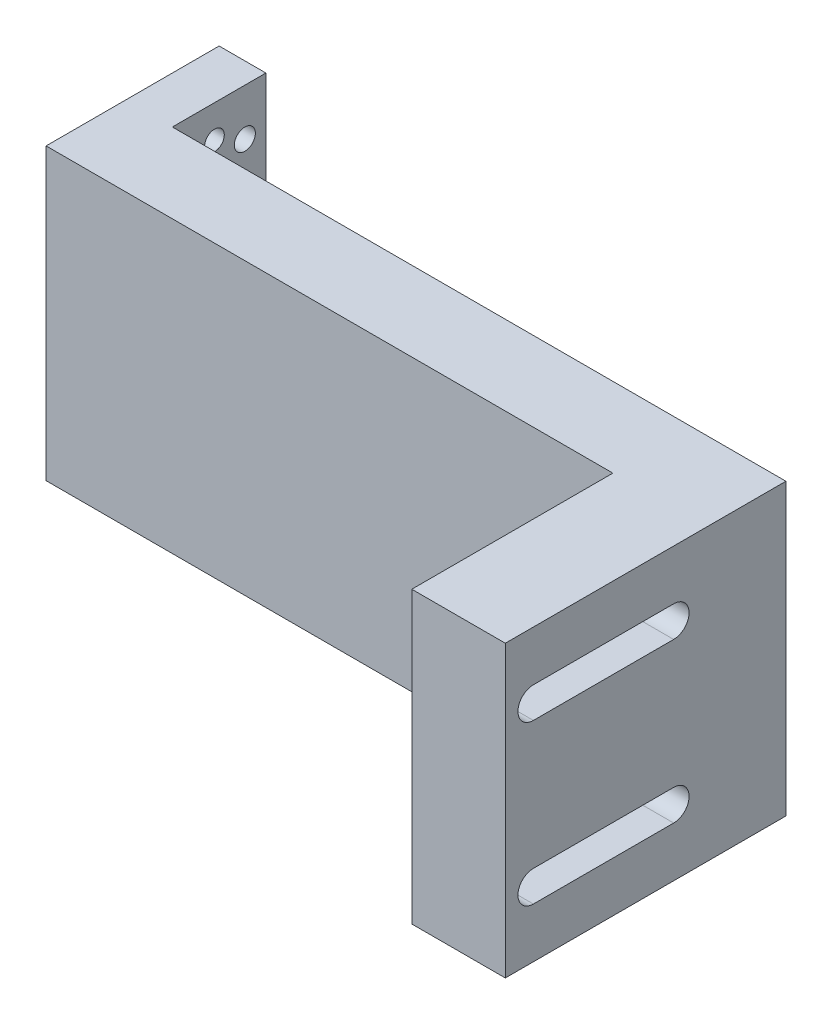
SolidWorks part; units mm, degrees
material "铝材"
ref_plane "前基準面" through (0, 0, 0) normal (0, 0, 1) x (1, 0, 0)
ref_plane "上基準面" through (0, 0, 0) normal (0, 1, 0) x (1, 0, 0)
ref_plane "右基準面" through (0, 0, 0) normal (1, 0, 0) x (0, 0, -1)
sketch "草图1" plane through (0, 0, 0) normal (0, 0, 1) x (1, 0, 0)
  line L1 (0, 0) -> (141.2, 0)
  line L2 (0, 0) -> (0, 62)
  line L3 (0, 62) -> (141.2, 62)
  line L4 (141.2, 0) -> (141.2, 62)
  dimension "D1" = 141.2
  dimension "D2" = 62
extrude "凸台-拉伸1" add sketch "草图1" along normal blind 80
sketch "草图2" plane through (0, 0, 0) normal (0, -1, 0) x (1, 0, 0)
  line L0 (0, 0) -> (141.2, 0) construction
  line L1 (10, 0) -> (141.2, 0)
  line L2 (10, 0) -> (10, 20)
  line L3 (10, 20) -> (141.2, 20)
  line L4 (141.2, 0) -> (141.2, 20)
  line L5 (141.2, 80) -> (141.2, 0) construction
  line L6 (0, 80) -> (0, 0) construction
  line L7 (0, 80) -> (121.2, 80)
  line L8 (0, 80) -> (0, 37)
  line L9 (0, 37) -> (121.2, 37)
  line L10 (121.2, 80) -> (121.2, 37)
  dimension "D1" = 10
  dimension "D2" = 20
  dimension "D3" = 17
  dimension "D4" = 20
extrude "切除-拉伸1" cut sketch "草图2" against normal through all
sketch "草图3" plane through (121.2, 0, 0) normal (-1, 0, 0) x (0, 0, 1)
  line L0 (44, 14) -> (74, 14) construction
  line L1 (44, 17.3) -> (74, 17.3)
  line L2 (44, 10.7) -> (74, 10.7)
  line L3 (80, 31) -> (37, 31) construction
  line L4 (80, 62) -> (80, 0) construction
  line L5 (37, 62) -> (37, 0) construction
  line L6 (44, 48) -> (74, 48) construction
  line L7 (44, 44.7) -> (74, 44.7)
  line L8 (44, 51.3) -> (74, 51.3)
  arc A0 (44, 17.3) -> (44, 10.7) centre (44, 14) ccw
  arc A1 (74, 10.7) -> (74, 17.3) centre (74, 14) ccw
  arc A2 (44, 44.7) -> (44, 51.3) centre (44, 48) cw
  arc A3 (74, 51.3) -> (74, 44.7) centre (74, 48) cw
  point P2 (59, 14)
  point P15 (59, 48)
  dimension "D2" = 6
  dimension "D1" = 6.6
  dimension "D3" = 30
  dimension "D4" = 34
extrude "切除-拉伸2" cut sketch "草图3" against normal blind 70
sketch "草图4" plane through (10, 0, 0) normal (1, 0, 0) x (0, 0, -1)
  line L0 (0, 31) -> (-20, 31) construction
  line L1 (0, 62) -> (0, 0) construction
  line L2 (-20, 62) -> (-20, 0) construction
  circle A0 centre (-4.5, 10) radius 2.25
  circle A1 centre (-4.5, 52) radius 2.25
  dimension "D1" = 4.5
  dimension "D2" = 4.5
  dimension "D3" = 42
extrude "切除-拉伸3" cut sketch "草图4" against normal through all
hole_wizard "M5 螺纹孔1" positions "草图6" profile "草图5" tap size "M5" standard "ISO"
sketch "草图6" plane through (0, 0, 0) normal (-1, 0, 0) x (0, 0, 1)
  point P0 (29, 7)
  point P1 (11, 7)
  point P4 (11, 55)
  point P7 (29, 55)
sketch "草图5" plane through (0, 7, 29) normal (0, 1, 0) x (0, 0, 1)
  line L0 (0, 0) -> (0, 13.6618)
  line L1 (0, 13.6618) -> (2.1, 12.4)
  line L2 (2.1, 12.4) -> (2.1, 0)
  line L5 (2.1, 0) -> (0, 0)
  line L10 (0, 13.6618) -> (-2.1, 12.4) construction
  line L11 (0, -6.35) -> (0, 107.95) construction
  dimension "螺纹孔钻头直径" = 4.2
  dimension "螺纹孔钻头深度" = 12.4
  dimension "导头角度" = 118
cosmetic thread "孔螺蚊线1" parameters "D1"=10, "D2"=5
cosmetic thread "孔螺蚊线2" parameters "D1"=10, "D2"=5
cosmetic thread "孔螺蚊线3" parameters "D1"=10, "D2"=5
cosmetic thread "孔螺蚊线4" parameters "D1"=10, "D2"=5
